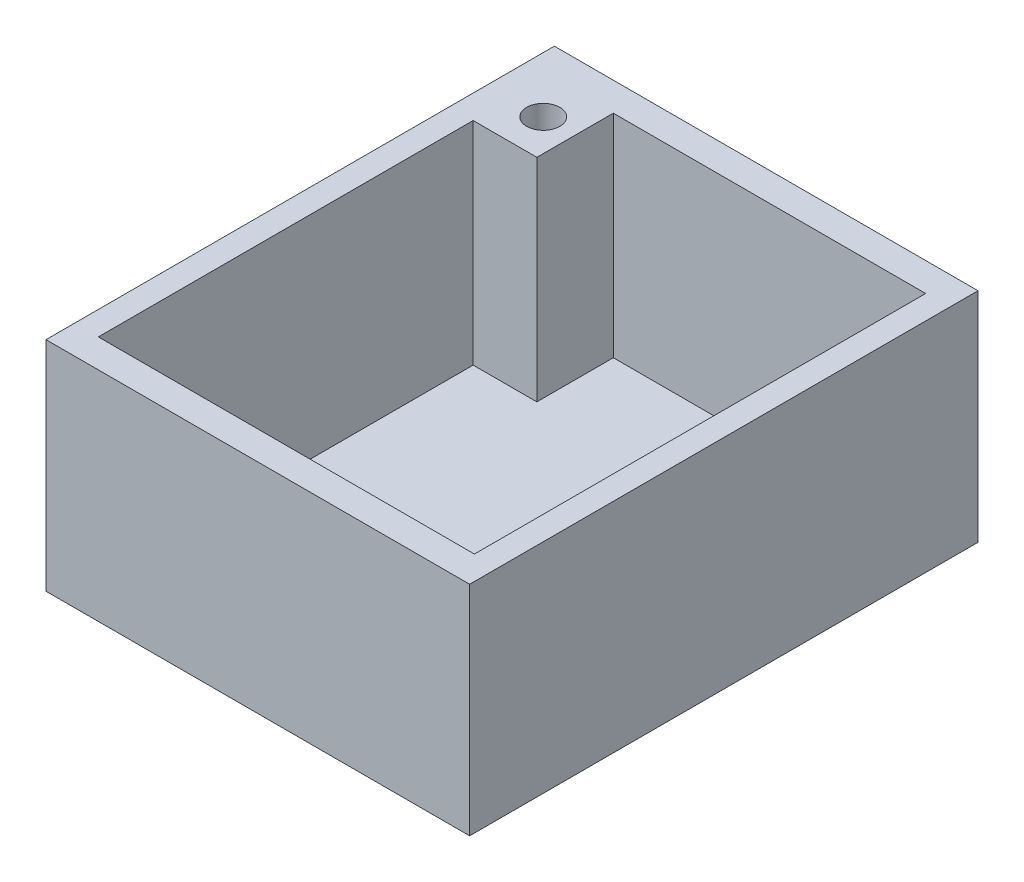
SolidWorks part; units mm, degrees
ref_plane "Спереди" through (0, 0, 0) normal (0, 0, 1) x (1, 0, 0)
ref_plane "Сверху" through (0, 0, 0) normal (0, 1, 0) x (1, 0, 0)
ref_plane "Справа" through (0, 0, 0) normal (1, 0, 0) x (0, 0, -1)
sketch "Эскиз1" plane through (0, 0, 0) normal (0, 1, 0) x (1, 0, 0)
  line L1 (0.0241, 60.0076) -> (50.0241, 60.0076)
  line L2 (0.0241, 60.0076) -> (0.0241, 0.0076)
  line L3 (0.0241, 0.0076) -> (50.0241, 0.0076)
  line L4 (50.0241, 60.0076) -> (50.0241, 0.0076)
  line L5 (0.0241, 60.0076) -> (50.0241, 0.0076) construction
  line L6 (0.0241, 0.0076) -> (50.0241, 60.0076) construction
  line L7 (2.8317, 56.6385) -> (47.2165, 56.6385)
  line L8 (2.8317, 56.6385) -> (2.8317, 3.3768)
  line L9 (2.8317, 3.3768) -> (47.2165, 3.3768)
  line L10 (47.2165, 56.6385) -> (47.2165, 3.3768)
  line L11 (2.8317, 56.6385) -> (47.2165, 3.3768) construction
  line L12 (2.8317, 3.3768) -> (47.2165, 56.6385) construction
  line L13 (10.3518, 47.6144) -> (2.8317, 47.6144)
  line L14 (10.3518, 47.6144) -> (10.3518, 56.6385)
  line L15 (10.3518, 56.6385) -> (2.8317, 56.6385)
  line L16 (2.8317, 47.6144) -> (2.8317, 56.6385)
  line L17 (10.3518, 47.6144) -> (2.8317, 56.6385) construction
  line L18 (10.3518, 56.6385) -> (2.8317, 47.6144) construction
  circle A0 centre (6.5918, 52.1264) radius 1.9535
  point P0 (25.0241, 30.0076)
  point P5 (6.5918, 52.1264)
  point P7 (25.0241, 30.0076)
extrude "Бобышка-Вытянуть1" add sketch "Эскиз1" along normal blind 25 contours L13 L14 L7 L8 A0 | L4 L1 L2 L3 L7 L10 L9 L8
sketch "Эскиз2" plane through (0, 0, -0.0076) normal (0, 0, 1) x (1, 0, 0)
  line L1 (0.0241, 0) -> (50.0241, 0)
  line L2 (0.0241, 0) -> (0.0241, -0.7169)
  line L3 (0.0241, -0.7169) -> (50.0241, -0.7169)
  line L4 (50.0241, 0) -> (50.0241, -0.7169)
extrude "Бобышка-Вытянуть2" add sketch "Эскиз2" against normal blind 60
